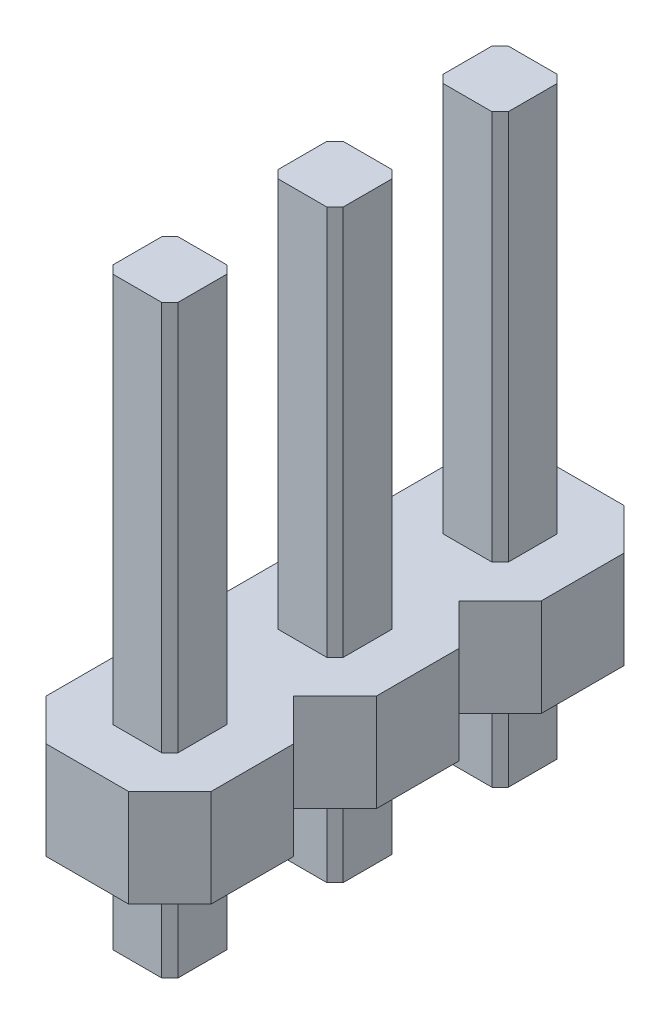
SolidWorks part; units mm, degrees
ref_plane "Plan de face" through (0, 0, 0) normal (0, 0, 1) x (1, 0, 0)
ref_plane "Plan de dessus" through (0, 0, 0) normal (0, 1, 0) x (1, 0, 0)
ref_plane "Plan de droite" through (0, 0, 0) normal (1, 0, 0) x (0, 0, -1)
sketch "Sketch1" plane through (0, 0, 0) normal (0, 1, 0) x (1, 0, 0)
  line L0 (-0.635, 10.16) -> (0.635, 10.16)
  line L1 (0.635, 10.16) -> (1.27, 9.525)
  line L2 (1.27, 9.525) -> (1.27, 8.255)
  line L3 (1.27, 8.255) -> (0.635, 7.62)
  line L4 (-0.635, 10.16) -> (-1.27, 9.525)
  line L5 (-1.27, 9.525) -> (-1.27, 8.255)
  line L6 (-1.27, 8.255) -> (-0.635, 7.62)
  line L7 (0.635, 7.62) -> (1.27, 6.985)
  line L8 (1.27, 6.985) -> (1.27, 5.715)
  line L9 (1.27, 5.715) -> (0.635, 5.08)
  line L10 (-0.635, 7.62) -> (-1.27, 6.985)
  line L11 (-1.27, 6.985) -> (-1.27, 5.715)
  line L12 (-1.27, 5.715) -> (-0.635, 5.08)
  line L13 (0.635, 5.08) -> (1.27, 4.445)
  line L14 (1.27, 4.445) -> (1.27, 3.175)
  line L15 (1.27, 3.175) -> (0.635, 2.54)
  line L16 (-0.635, 5.08) -> (-1.27, 4.445)
  line L17 (-1.27, 4.445) -> (-1.27, 3.175)
  line L18 (-1.27, 3.175) -> (-0.635, 2.54)
  line L19 (0.635, 2.54) -> (1.27, 1.905)
  line L20 (1.27, 1.905) -> (1.27, 0.635)
  line L21 (1.27, 0.635) -> (0.635, 0)
  line L22 (-0.635, 2.54) -> (-1.27, 1.905)
  line L23 (-1.27, 1.905) -> (-1.27, 0.635)
  line L24 (-1.27, 0.635) -> (-0.635, 0)
  line L25 (0.635, 0) -> (1.27, -0.635)
  line L26 (1.27, -0.635) -> (1.27, -1.905)
  line L27 (1.27, -1.905) -> (0.635, -2.54)
  line L28 (-0.635, 0) -> (-1.27, -0.635)
  line L29 (-1.27, -0.635) -> (-1.27, -1.905)
  line L30 (-1.27, -1.905) -> (-0.635, -2.54)
  line L31 (0.635, -2.54) -> (1.27, -3.175)
  line L32 (1.27, -3.175) -> (1.27, -4.445)
  line L33 (1.27, -4.445) -> (0.635, -5.08)
  line L34 (-0.635, -2.54) -> (-1.27, -3.175)
  line L35 (-1.27, -3.175) -> (-1.27, -4.445)
  line L36 (-1.27, -4.445) -> (-0.635, -5.08)
  line L50 (-0.635, 7.62) -> (0.635, 7.62) construction
  line L51 (0, 10.16) -> (0, 7.62) construction
  line L52 (-0.635, -5.08) -> (0.635, -5.08)
  point P0 (0, 8.89)
  point P1 (0, 8.89)
  point P54 (0, 8.89)
extrude "Boss-Extrude1" add sketch "Sketch1" along normal blind 1.5
sketch "Sketch3" plane through (0, 1.5, 0) normal (0, 1, 0) x (1, 0, 0)
  line L0 (-1.27, 8.89) -> (1.27, 8.89) construction
  line L1 (-1.27, 9.525) -> (-1.27, 8.255) construction
  line L2 (1.27, 8.255) -> (1.27, 9.525) construction
  line L3 (0.375, 9.39) -> (0.5, 9.265)
  line L4 (-0.375, 9.39) -> (0.375, 9.39)
  line L5 (-0.5, 9.265) -> (-0.5, 8.515)
  line L6 (-0.375, 8.39) -> (0.375, 8.39)
  line L7 (0.5, 9.265) -> (0.5, 8.515)
  line L8 (-0.5, 9.39) -> (0.5, 8.39) construction
  line L9 (-0.5, 8.39) -> (0.5, 9.39) construction
  line L10 (0.375, 8.39) -> (0.5, 8.515)
  line L11 (-0.5, 8.515) -> (-0.375, 8.39)
  line L12 (-0.5, 9.265) -> (-0.375, 9.39)
  line L13 (0.375, 6.85) -> (0.5, 6.725)
  line L14 (-0.375, 6.85) -> (0.375, 6.85)
  line L15 (-0.5, 6.725) -> (-0.5, 5.975)
  line L16 (-0.375, 5.85) -> (0.375, 5.85)
  line L17 (0.5, 6.725) -> (0.5, 5.975)
  line L18 (0.375, 5.85) -> (0.5, 5.975)
  line L19 (-0.5, 5.975) -> (-0.375, 5.85)
  line L20 (-0.5, 6.725) -> (-0.375, 6.85)
  line L21 (-1.27, 6.35) -> (1.27, 6.35) construction
  line L22 (-0.5, 6.85) -> (0.5, 5.85) construction
  line L23 (-0.5, 5.85) -> (0.5, 6.85) construction
  line L24 (0.375, 4.31) -> (0.5, 4.185)
  line L25 (-0.375, 4.31) -> (0.375, 4.31)
  line L26 (-0.5, 4.185) -> (-0.5, 3.435)
  line L27 (-0.375, 3.31) -> (0.375, 3.31)
  line L28 (0.5, 4.185) -> (0.5, 3.435)
  line L29 (0.375, 3.31) -> (0.5, 3.435)
  line L30 (-0.5, 3.435) -> (-0.375, 3.31)
  line L31 (-0.5, 4.185) -> (-0.375, 4.31)
  line L32 (-1.27, 3.81) -> (1.27, 3.81) construction
  line L33 (-0.5, 4.31) -> (0.5, 3.31) construction
  line L34 (-0.5, 3.31) -> (0.5, 4.31) construction
  line L35 (0.375, 1.77) -> (0.5, 1.645)
  line L36 (-0.375, 1.77) -> (0.375, 1.77)
  line L37 (-0.5, 1.645) -> (-0.5, 0.895)
  line L38 (-0.375, 0.77) -> (0.375, 0.77)
  line L39 (0.5, 1.645) -> (0.5, 0.895)
  line L40 (0.375, 0.77) -> (0.5, 0.895)
  line L41 (-0.5, 0.895) -> (-0.375, 0.77)
  line L42 (-0.5, 1.645) -> (-0.375, 1.77)
  line L43 (-1.27, 1.27) -> (1.27, 1.27) construction
  line L44 (-0.5, 1.77) -> (0.5, 0.77) construction
  line L45 (-0.5, 0.77) -> (0.5, 1.77) construction
  line L46 (0.375, -0.77) -> (0.5, -0.895)
  line L47 (-0.375, -0.77) -> (0.375, -0.77)
  line L48 (-0.5, -0.895) -> (-0.5, -1.645)
  line L49 (-0.375, -1.77) -> (0.375, -1.77)
  line L50 (0.5, -0.895) -> (0.5, -1.645)
  line L51 (0.375, -1.77) -> (0.5, -1.645)
  line L52 (-0.5, -1.645) -> (-0.375, -1.77)
  line L53 (-0.5, -0.895) -> (-0.375, -0.77)
  line L54 (-1.27, -1.27) -> (1.27, -1.27) construction
  line L55 (-0.5, -0.77) -> (0.5, -1.77) construction
  line L56 (-0.5, -1.77) -> (0.5, -0.77) construction
  line L57 (0.375, -3.31) -> (0.5, -3.435)
  line L58 (-0.375, -3.31) -> (0.375, -3.31)
  line L59 (-0.5, -3.435) -> (-0.5, -4.185)
  line L60 (-0.375, -4.31) -> (0.375, -4.31)
  line L61 (0.5, -3.435) -> (0.5, -4.185)
  line L62 (0.375, -4.31) -> (0.5, -4.185)
  line L63 (-0.5, -4.185) -> (-0.375, -4.31)
  line L64 (-0.5, -3.435) -> (-0.375, -3.31)
  line L65 (-1.27, -3.81) -> (1.27, -3.81) construction
  line L66 (-0.5, -3.31) -> (0.5, -4.31) construction
  line L67 (-0.5, -4.31) -> (0.5, -3.31) construction
  point P6 (0, 8.89)
  point P22 (0, 6.35)
  point P37 (0, 3.81)
  point P52 (0, 1.27)
  point P67 (0, -1.27)
  point P82 (0, -3.81)
  dimension "D1" = 1
  dimension "D2" = 1
  dimension "D3" = 6
extrude "Boss-Extrude2" add sketch "Sketch3" along normal blind 6 and the other way blind 3
sketch "Sketch4" plane through (0, 0, 0) normal (0, 1, 0) x (1, 0, 0)
  line L0 (0.635, 2.54) -> (-0.635, 2.54)
  line L1 (-0.635, 2.54) -> (-3.5513, 2.1454)
  line L2 (-3.5513, 2.1454) -> (-3.5513, -5.549)
  line L3 (-3.5513, -5.549) -> (3.5184, -6.3053)
  line L4 (3.5184, -6.3053) -> (3.5184, 1.3234)
  line L5 (3.5184, 1.3234) -> (0.635, 2.54)
extrude "Cut-Extrude1" cut sketch "Sketch4" against normal through all and the other way through all
